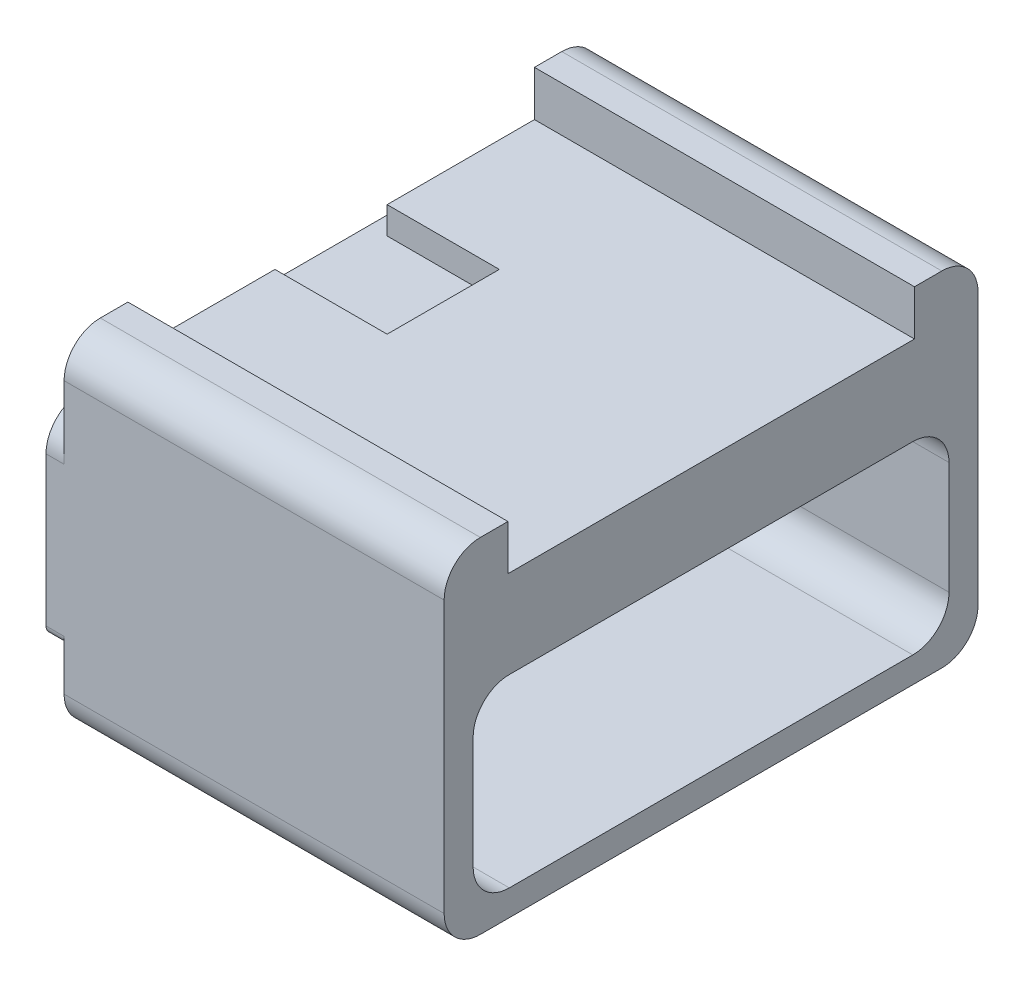
SolidWorks part; units mm, degrees
ref_plane "Front Plane" through (0, 0, 0) normal (0, 0, 1) x (1, 0, 0)
ref_plane "Top Plane" through (0, 0, 0) normal (0, 1, 0) x (1, 0, 0)
ref_plane "Right Plane" through (0, 0, 0) normal (1, 0, 0) x (0, 0, -1)
sketch "Sketch3" plane through (0, 0, 0) normal (1, 0, 0) x (0, 0, -1)
  line L0 (-12.75, -9.5) -> (12.75, -9.5)
  line L1 (-14.75, -7.5) -> (-14.75, 7.5)
  line L2 (-12.75, 9.5) -> (12.75, 9.5)
  line L3 (14.75, -7.5) -> (14.75, 7.5)
  line L4 (0, 9.5) -> (0, -9.5) construction
  line L5 (14.75, 0) -> (-14.75, 0) construction
  arc A0 (14.75, -7.5) -> (12.75, -9.5) centre (12.75, -7.5) cw
  arc A1 (-14.75, -7.5) -> (-12.75, -9.5) centre (-12.75, -7.5) ccw
  arc A2 (-12.75, 9.5) -> (-14.75, 7.5) centre (-12.75, 7.5) ccw
  arc A3 (12.75, 9.5) -> (14.75, 7.5) centre (12.75, 7.5) cw
  point P16 (0, 0)
  dimension "D3" = 2
  dimension "D1" = 19
  dimension "D2" = 25.5
extrude "Boss-Extrude1" add sketch "Sketch3" along normal blind 21
sketch "Sketch5" plane through (0, 9.5, 0) normal (0, 1, 0) x (1, 0, 0)
  line L0 (0, 12.75) -> (0, -12.75) construction
  line L1 (6.2, 3.1) -> (0, 3.1)
  line L2 (6.2, 3.1) -> (6.2, -3.1)
  line L3 (6.2, -3.1) -> (0, -3.1)
  line L4 (0, 3.1) -> (0, -3.1)
  line L5 (6.2, 0) -> (0, 0) construction
  dimension "D1" = 6.2
  dimension "D2" = 6.2
extrude "Cut-Extrude1" cut sketch "Sketch5" against normal blind 4
sketch "Sketch7" plane through (0, 0, 0) normal (-1, 0, 0) x (0, 0, 1)
  line L0 (0, 2.1353) -> (0, -8.0729) construction
  line L1 (-11.1476, -8.0729) -> (11.1476, -8.0729)
  line L2 (-13.1476, -6.0729) -> (-13.1476, 0.1353)
  line L3 (-11.1476, 2.1353) -> (11.1476, 2.1353)
  line L4 (13.1476, -6.0729) -> (13.1476, 0.1353)
  line L5 (12.75, -9.5) -> (-12.75, -9.5) construction
  arc A0 (11.1476, -8.0729) -> (13.1476, -6.0729) centre (11.1476, -6.0729) ccw
  arc A1 (11.1476, 2.1353) -> (13.1476, 0.1353) centre (11.1476, 0.1353) cw
  arc A2 (-13.1476, 0.1353) -> (-11.1476, 2.1353) centre (-11.1476, 0.1353) cw
  arc A3 (-13.1476, -6.0729) -> (-11.1476, -8.0729) centre (-11.1476, -6.0729) ccw
  point P6 (0, -2.9688)
  point P7 (0, -9.5)
  dimension "D1" = 2
extrude "Cut-Extrude2" cut sketch "Sketch7" against normal through all both and the other way through all
sketch "Sketch9" plane through (0, 9.5, 0) normal (0, 1, 0) x (1, 0, 0)
  line L0 (0, 12.75) -> (0, 3.1) construction
  line L1 (0, 11.24) -> (24.2849, 11.24)
  line L2 (0, 11.24) -> (0, -11.2248)
  line L3 (0, -11.2248) -> (24.2849, -11.2248)
  line L4 (24.2849, 11.24) -> (24.2849, -11.2248)
  line L5 (24.2849, 0.0076) -> (0, 0.0076) construction
  line L6 (6.2, -3.1) -> (6.2, 3.1) construction
  point P8 (6.2, 0)
  point P12 (6.2, -0.2283)
extrude "Cut-Extrude3" cut sketch "Sketch9" against normal blind 2.5
sketch "Sketch10" plane through (21, 0, 0) normal (1, 0, 0) x (0, 0, -1)
  line L1 (-15.9191, 11.2845) -> (15.8968, 11.2845)
  line L2 (-15.9191, 11.2845) -> (-15.9191, -10.3889)
  line L3 (-15.9191, -10.3889) -> (15.8968, -10.3889)
  line L4 (15.8968, 11.2845) -> (15.8968, -10.3889)
sketch "Sketch11" plane through (0, 0, 0) normal (-1, 0, 0) x (0, 0, 1)
  line L0 (-13.6476, -5.2351) -> (-14.25, -5.2351)
  line L1 (-13.1476, 0.1353) -> (-13.1476, -6.0729) construction
  line L2 (-14.75, -7.5) -> (-14.75, 7.5) construction
  line L3 (-14.75, -4.7351) -> (-14.75, 3.5)
  line L4 (-12.75, 5.5) -> (12.75, 5.5)
  line L5 (14.75, 7.5) -> (14.75, -7.5) construction
  line L6 (14.75, 3.5) -> (14.75, -4.7351)
  line L7 (14.25, -5.2351) -> (13.6476, -5.2351)
  line L8 (13.1476, -6.0729) -> (13.1476, 0.1353) construction
  line L9 (-13.1476, -4.7351) -> (-13.1476, 0.1353)
  line L10 (-11.1476, 2.1353) -> (11.1476, 2.1353)
  line L11 (13.1476, 0.1353) -> (13.1476, -4.7351)
  line L12 (-3.1, 5.5) -> (3.1, 5.5) construction
  line L13 (11.1476, 2.1353) -> (-11.1476, 2.1353) construction
  arc A0 (11.1476, 2.1353) -> (13.1476, 0.1353) centre (11.1476, 0.1353) cw
  arc A1 (-13.1476, 0.1353) -> (-11.1476, 2.1353) centre (-11.1476, 0.1353) cw
  arc A2 (12.75, 5.5) -> (14.75, 3.5) centre (12.75, 3.5) cw
  arc A3 (-14.75, 3.5) -> (-12.75, 5.5) centre (-12.75, 3.5) cw
  arc A4 (13.6476, -5.2351) -> (13.1476, -4.7351) centre (13.6476, -4.7351) cw
  arc A5 (-13.6476, -5.2351) -> (-13.1476, -4.7351) centre (-13.6476, -4.7351) ccw
  arc A6 (14.75, -4.7351) -> (14.25, -5.2351) centre (14.25, -4.7351) cw
  arc A7 (-14.25, -5.2351) -> (-14.75, -4.7351) centre (-14.25, -4.7351) cw
  point P26 (14.75, 5.5)
  point P29 (-14.75, 5.5)
  point P32 (13.1476, -5.2351)
  point P35 (-13.1476, -5.2351)
  point P38 (14.75, -5.2351)
  point P41 (-14.75, -5.2351)
  dimension "D1" = 2
  dimension "D2" = 2
  dimension "D3" = 0.5
extrude "Boss-Extrude2" add sketch "Sketch11" along normal blind 1
